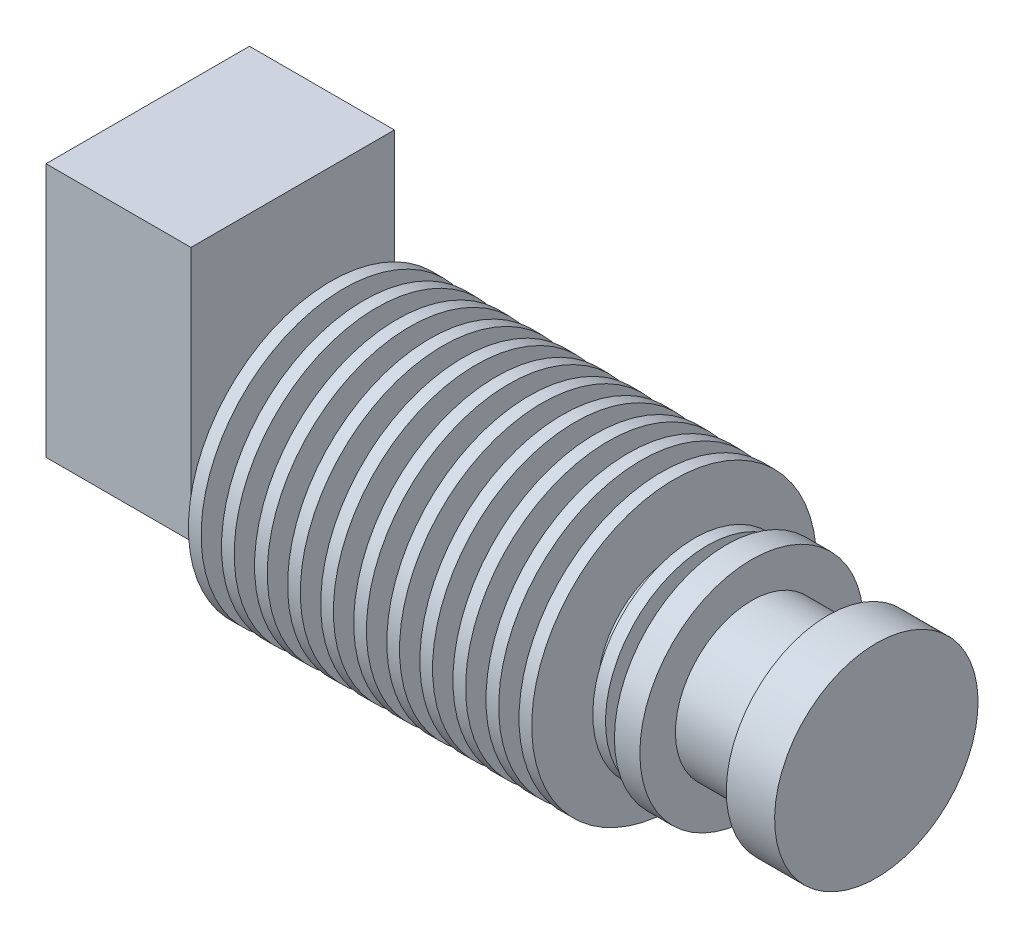
SolidWorks part; units mm, degrees
ref_plane "前基準面" through (0, 0, 0) normal (0, 0, 1) x (1, 0, 0)
ref_plane "上基準面" through (0, 0, 0) normal (0, 1, 0) x (1, 0, 0)
ref_plane "右基準面" through (0, 0, 0) normal (1, 0, 0) x (0, 0, -1)
sketch "草圖1" plane through (0, 0, 0) normal (0, 0, 1) x (1, 0, 0)
  line L0 (0, 0) -> (-26, 0) construction
  line L1 (-26, 0) -> (-26, 11.2)
  line L2 (-26, 11.2) -> (-25, 11.2)
  line L3 (-25, 11.2) -> (-25, 6)
  line L4 (-25, 6) -> (-23.4, 6)
  line L5 (-23.4, 6) -> (-23.4, 11.2)
  line L6 (-22.4, 11.2) -> (-22.4, 6)
  line L7 (-22.4, 6) -> (-20.8, 6)
  line L8 (-23.4, 11.2) -> (-22.4, 11.2)
  line L9 (-20.8, 6) -> (-20.8, 11.2)
  line L10 (-19.8, 11.2) -> (-19.8, 6)
  line L11 (-19.8, 6) -> (-18.2, 6)
  line L12 (-20.8, 11.2) -> (-19.8, 11.2)
  line L13 (-18.2, 6) -> (-18.2, 11.2)
  line L14 (-17.2, 11.2) -> (-17.2, 6)
  line L15 (-17.2, 6) -> (-15.6, 6)
  line L16 (-18.2, 11.2) -> (-17.2, 11.2)
  line L17 (-15.6, 6) -> (-15.6, 11.2)
  line L18 (-14.6, 11.2) -> (-14.6, 6)
  line L19 (-14.6, 6) -> (-13, 6)
  line L20 (-15.6, 11.2) -> (-14.6, 11.2)
  line L21 (-13, 6) -> (-13, 11.2)
  line L22 (-12, 11.2) -> (-12, 6)
  line L23 (-12, 6) -> (-10.4, 6)
  line L24 (-13, 11.2) -> (-12, 11.2)
  line L25 (-10.4, 6) -> (-10.4, 11.2)
  line L26 (-9.4, 11.2) -> (-9.4, 6)
  line L27 (-9.4, 6) -> (-7.8, 6)
  line L28 (-10.4, 11.2) -> (-9.4, 11.2)
  line L29 (-7.8, 6) -> (-7.8, 11.2)
  line L30 (-6.8, 11.2) -> (-6.8, 6)
  line L31 (-6.8, 6) -> (-5.2, 6)
  line L32 (-7.8, 11.2) -> (-6.8, 11.2)
  line L33 (-5.2, 6) -> (-5.2, 11.2)
  line L34 (-4.2, 11.2) -> (-4.2, 6)
  line L35 (-4.2, 6) -> (-2.6, 6)
  line L36 (-5.2, 11.2) -> (-4.2, 11.2)
  line L37 (-2.6, 6) -> (-2.6, 11.2)
  line L38 (-1.6, 11.2) -> (-1.6, 6)
  line L39 (-1.6, 6) -> (0, 6)
  line L40 (-2.6, 11.2) -> (-1.6, 11.2)
  line L42 (0, 0) -> (-26, 0)
  line L43 (0, 6) -> (0, 11.2)
  line L44 (0, 11.2) -> (1, 11.2)
  line L45 (1, 11.2) -> (1, 6)
  line L46 (1, 0) -> (0, 0)
  line L47 (1, 6) -> (2.6, 6)
  line L49 (1, 0) -> (2.6, 0)
  line L50 (2.6, 6) -> (2.6, 0)
  dimension "D1" = 5.2
  dimension "D2" = 11.2
  dimension "D3" = 1
  dimension "D4" = 1.6
  dimension "D5" = 6
  dimension "D7" = 1
  dimension "D8" = 1.6
  dimension "D6" = 10
revolve "旋轉1" add sketch "草圖1" angle 360 about L0
sketch "草圖2" plane through (0, 0, 0) normal (0, 0, 1) x (1, 0, 0)
  line L0 (2.6, 0) -> (2.6, 8)
  line L1 (2.6, 8) -> (3.6, 8)
  line L2 (3.6, 8) -> (3.6, 6)
  line L3 (3.6, 6) -> (5.1, 6)
  line L4 (5.1, 6) -> (5.1, 8.7981)
  line L5 (5.1, 8.7981) -> (7.1, 8.7981)
  line L6 (7.1, 8.7981) -> (7.1, 6)
  line L7 (7.1, 6) -> (13.1, 6)
  line L8 (13.1, 6) -> (13.1, 8)
  line L9 (13.1, 8) -> (16.9, 8)
  line L10 (16.9, 8) -> (16.9, 0)
  line L11 (16.9, 0) -> (2.6, 0)
  line L14 (2.6, -6) -> (2.6, 6) construction
  point P15 (0, 0)
  dimension "D1" = 8
  dimension "D2" = 1
  dimension "D3" = 1.5
  dimension "D4" = 2
  dimension "D5" = 6
  dimension "D6" = 3.8
  dimension "D7" = 8
  dimension "D8" = 6
  dimension "D9" = 6
revolve "旋轉2" add sketch "草圖2" angle 360 about L11
sketch "草圖3" plane through (-26, 0, 0) normal (-1, 0, 0) x (0, 0, 1)
  circle A0 centre (0, 0) radius 3.5
extrude "填料-伸長1" add sketch "草圖3" along normal blind 3
sketch "草圖4" plane through (-29, 0, 0) normal (-1, 0, 0) x (0, 0, 1)
  line L1 (8, 16) -> (-8, 16)
  line L2 (8, 16) -> (8, -4)
  line L3 (8, -4) -> (-8, -4)
  line L4 (-8, 16) -> (-8, -4)
  dimension "D1" = 20
  dimension "D2" = 16
  dimension "D3" = 8
  dimension "D4" = 4
extrude "填料-伸長2" add sketch "草圖4" along normal blind 11.4
sketch "草圖5" plane through (-40.4, 0, 0) normal (-1, 0, 0) x (0, 0, 1)
  line L1 (4.0415, 0) -> (2.0207, 3.5)
  line L2 (2.0207, 3.5) -> (-2.0207, 3.5)
  line L3 (-2.0207, 3.5) -> (-4.0415, 0)
  line L4 (-4.0415, 0) -> (-2.0207, -3.5)
  line L5 (-2.0207, -3.5) -> (2.0207, -3.5)
  line L6 (2.0207, -3.5) -> (4.0415, 0)
  circle A0 centre (0, 0) radius 3.5 construction
  dimension "D1" = 7
extrude "填料-伸長3" add sketch "草圖5" along normal blind 3
sketch "草圖6" plane through (-43.4, 0, 0) normal (-1, 0, 0) x (0, 0, 1)
  circle A0 centre (0, 0) radius 1.8
  dimension "D1" = 3.6
ref_plane "平面1" through (-45.4, 0, 0) normal (-1, 0, 0) x (0, 0, 1)
sketch "草圖7" plane through (-45.4, 0, 0) normal (-1, 0, 0) x (0, 0, 1)
  circle A0 centre (0, 0) radius 0.5
  dimension "D1" = 1
loft "疊層拉伸1" add profiles "草圖6", "草圖7"
